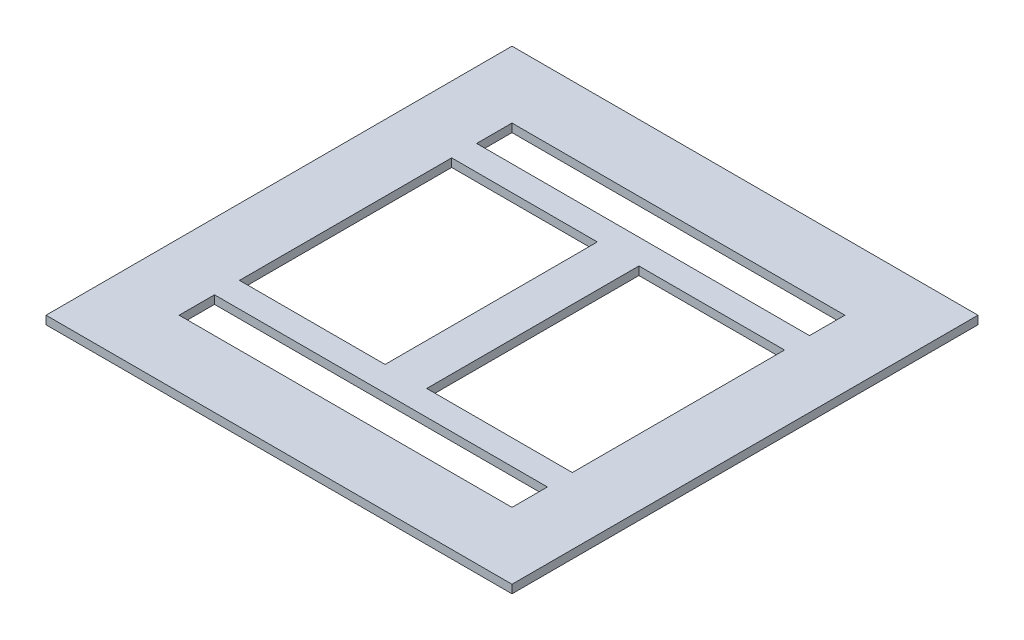
SolidWorks part; units mm, degrees
ref_plane "Front Plane" through (0, 0, 0) normal (0, 0, 1) x (1, 0, 0)
ref_plane "Top Plane" through (0, 0, 0) normal (0, 1, 0) x (1, 0, 0)
ref_plane "Right Plane" through (0, 0, 0) normal (1, 0, 0) x (0, 0, -1)
sketch "Sketch4" plane through (0, 0, 0) normal (0, 1, 0) x (1, 0, 0)
  line L25 (-56, 56) -> (56, 56)
  line L29 (-56, 56) -> (-56, -56)
  line L30 (-56, -56) -> (56, -56)
  line L31 (56, 56) -> (56, -56)
  line L79 (5, 25.5) -> (5, -25.5)
  line L83 (-40, -31.5) -> (-40, -40)
  line L86 (-5, 25.5) -> (-5, -25.5)
  line L87 (-5, -25.5) -> (-40, -25.5)
  line L89 (-40, -40) -> (40, -40)
  line L90 (40, -40) -> (40, -31.5)
  line L94 (-40, 31.5) -> (40, 31.5)
  line L96 (-40, 25.5) -> (-40, -25.5)
  line L97 (40, 40) -> (40, 31.5)
  line L105 (-5, 25.5) -> (-40, 25.5)
  line L107 (5, 25.5) -> (40, 25.5)
  line L109 (40, -25.5) -> (5, -25.5)
  line L110 (40, 40) -> (-40, 40)
  line L111 (-40, 40) -> (-40, 31.5)
  line L113 (-40, -31.5) -> (40, -31.5)
  line L115 (40, 25.5) -> (40, -25.5)
  point P4 (0, 0)
  point P5 (0, 0)
  point P78 (22.2959, 0)
  point P93 (-22.7041, -0.0367)
  point P110 (0, -35.75)
  point P172 (0, 35.75)
  dimension "D2" = 35
  dimension "D3" = 35
  dimension "D4" = 112
  dimension "D5" = 6
  dimension "D9" = 10
  dimension "D13" = 112
extrude "Boss-Extrude1" add sketch "Sketch4" along normal blind 2
